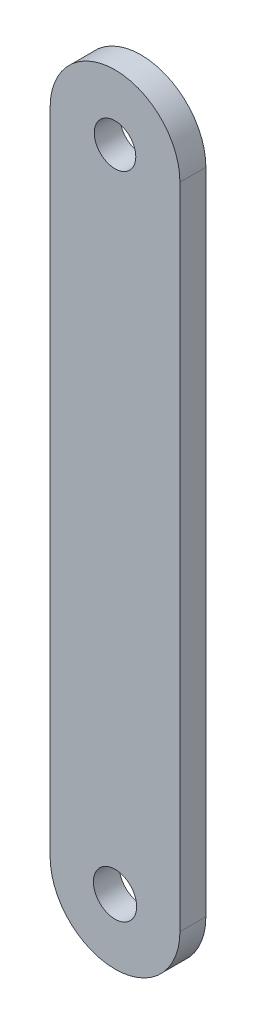
SolidWorks part; units mm, degrees
ref_plane "Front Plane" through (0, 0, 0) normal (0, 0, 1) x (1, 0, 0)
ref_plane "Top Plane" through (0, 0, 0) normal (0, 1, 0) x (1, 0, 0)
ref_plane "Right Plane" through (0, 0, 0) normal (1, 0, 0) x (0, 0, -1)
sketch "Sketch1" plane through (0, 0, 0) normal (0, 0, 1) x (1, 0, 0)
  line L2 (185.8254, 60.5329) -> (185.8254, 135.5329)
  line L4 (200.8254, 60.5329) -> (200.8254, 135.5329)
  arc A0 (185.8254, 60.5329) -> (200.8254, 60.5329) centre (193.3254, 60.5329) ccw
  arc A1 (200.8254, 135.5329) -> (185.8254, 135.5329) centre (193.3254, 135.5329) ccw
  circle A2 centre (193.3254, 60.5329) radius 2.5
  circle A3 centre (193.3254, 135.5329) radius 2.4
  dimension "D3" = 4.8
  dimension "D4" = 5
  dimension "D1" = 15
  dimension "D2" = 75
extrude "Boss-Extrude1" add sketch "Sketch1" along normal blind 3
